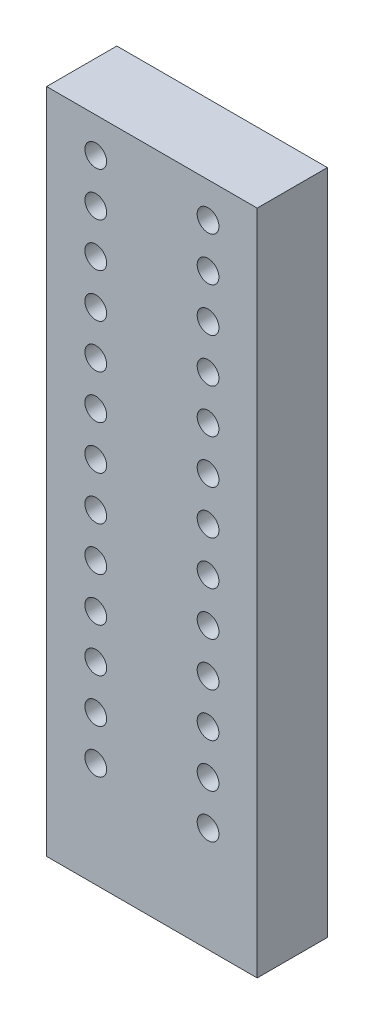
SolidWorks part; units mm, degrees
material "Alliage 1060"
ref_plane "Front" through (0, 0, 0) normal (0, 0, 1) x (1, 0, 0)
ref_plane "Top" through (0, 0, 0) normal (0, 1, 0) x (1, 0, 0)
ref_plane "Right" through (0, 0, 0) normal (1, 0, 0) x (0, 0, -1)
sketch "Esquisse1" plane through (0, 0, 0) normal (0, 0, 1) x (1, 0, 0)
  line L1 (-30, -95) -> (30, -95)
  line L2 (-30, -95) -> (-30, 95)
  line L3 (-30, 95) -> (30, 95)
  line L4 (30, -95) -> (30, 95)
  line L5 (-30, -95) -> (30, 95) construction
  line L6 (-30, 95) -> (30, -95) construction
  point P0 (0, 0)
  dimension "D1" = 60
  dimension "D2" = 190
extrude "Boss.-Extru.1" add sketch "Esquisse1" along normal blind 20
hole_wizard "Trou pour taraudage pour trou taraudé M61" positions "Esquisse2" profile "Esquisse3" hole size "M6" standard "ISO"
sketch "Esquisse2" plane through (0, -95, 0) normal (0, -1, 0) x (-1, 0, 0)
  line L0 (0, 0) -> (0, -20) construction
  line L1 (30, 0) -> (-30, 0) construction
  line L2 (30, -20) -> (-30, -20) construction
  line L4 (20, -10) -> (-20, -10) construction
  point P0 (-20, -10)
  point P2 (20, -10)
  point P14 (0, -10)
  point P15 (0, -10)
  dimension "D1" = 40
sketch "Esquisse3" plane through (20, -95, 10) normal (1, 0, 0) x (0, 0, -1)
  line L0 (0, 0) -> (0, 16.5022)
  line L1 (0, 16.5022) -> (2.5, 15)
  line L2 (2.5, 15) -> (2.5, 0)
  line L5 (2.5, 0) -> (0, 0)
  line L10 (0, 16.5022) -> (-2.5, 15) construction
  line L11 (0, -6.35) -> (0, 107.95) construction
  dimension "Diamètre du perçage" = 5
  dimension "Profondeur du perçage" = 15
  dimension "Angle de pointe" = 118
hole_wizard "Dégagement M61" positions "Esquisse6" profile "Esquisse7" hole size "M6" standard "ISO" end condition through all
sketch "Esquisse6" plane through (0, 0, 20) normal (0, 0, 1) x (1, 0, 0)
  line L0 (0, 0) -> (0, -95) construction
  line L1 (-30, -95) -> (30, -95) construction
  line L3 (-16, -65) -> (16, -65) construction
  point P0 (-16, -65)
  point P2 (16, -65)
  point P16 (0, -65)
  dimension "D1" = 32
  dimension "D2" = 30
sketch "Esquisse7" plane through (-16, -65, 20) normal (1, 0, 0) x (0, -1, 0)
  line L0 (0, 0) -> (0, 20)
  line L1 (0, 20) -> (3.1, 20)
  line L2 (3.1, 20) -> (3.1, 0)
  line L5 (3.1, 0) -> (0, 0)
  line L11 (0, -6.35) -> (0, 107.95) construction
  dimension "Diamètre du perçage jusqu'au prochain" = 6.2
  dimension "Profondeur du perçage jusqu'au prochain" = 20
pattern_linear "Répétition linéaire1" count 13 spacing 12.5 along (0, 1, 0) of "Dégagement M61"
